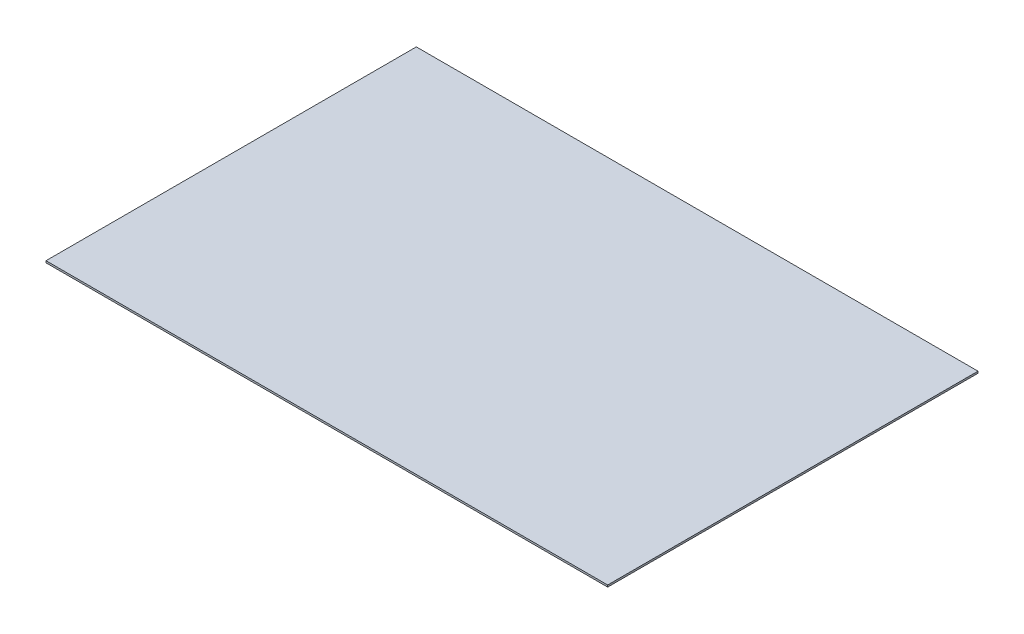
SolidWorks part; units mm, degrees
ref_plane "Front Plane" through (0, 0, 0) normal (0, 0, 1) x (1, 0, 0)
ref_plane "Top Plane" through (0, 0, 0) normal (0, 1, 0) x (1, 0, 0)
ref_plane "Right Plane" through (0, 0, 0) normal (1, 0, 0) x (0, 0, -1)
sketch "Sketch1" plane through (0, 0, 0) normal (0, 1, 0) x (1, 0, 0)
  line L1 (-203.9477, 347.3474) -> (706.0523, 347.3474)
  line L2 (-203.9477, 347.3474) -> (-203.9477, -252.6526)
  line L3 (-203.9477, -252.6526) -> (706.0523, -252.6526)
  line L4 (706.0523, 347.3474) -> (706.0523, -252.6526)
  dimension "D1" = 910
  dimension "D2" = 600
extrude "Boss-Extrude1" add sketch "Sketch1" along normal blind 3
